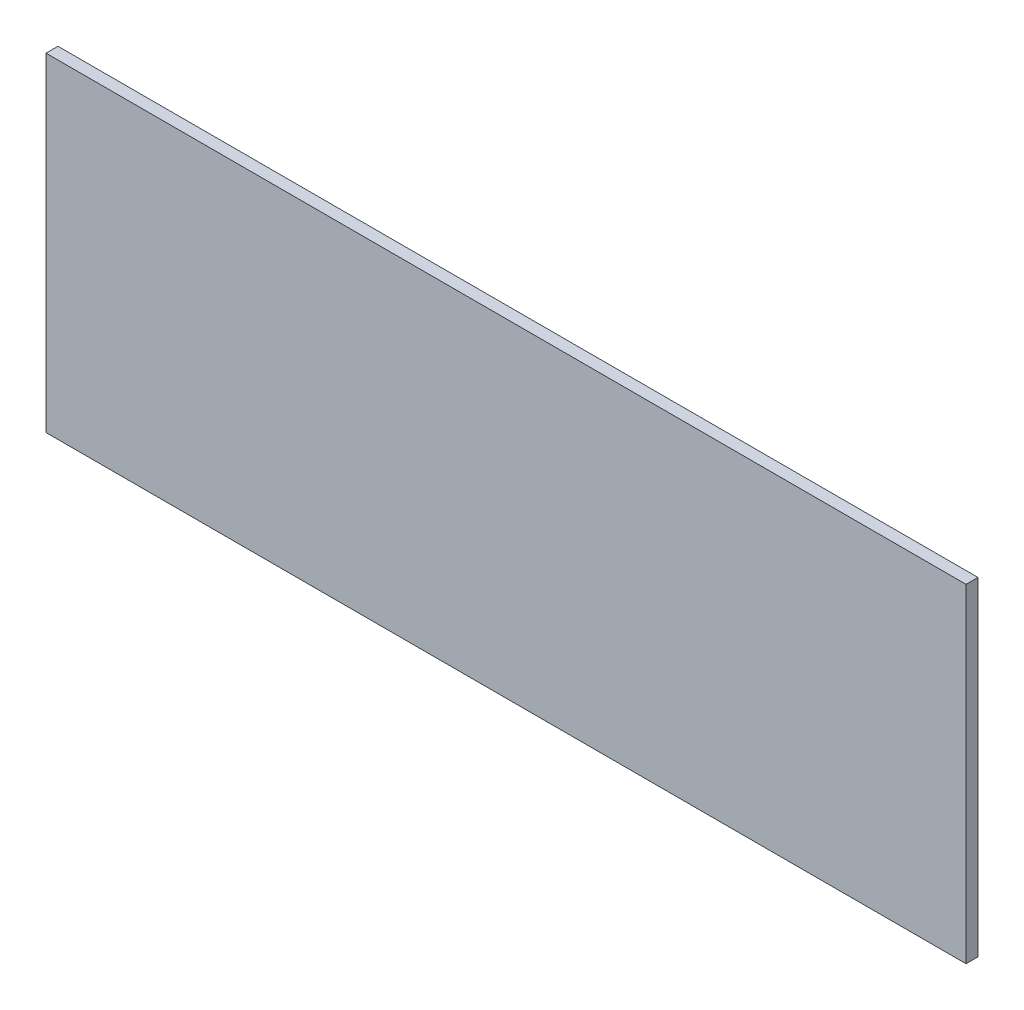
SolidWorks part; units mm, degrees
ref_plane "Front Plane" through (0, 0, 0) normal (0, 0, 1) x (1, 0, 0)
ref_plane "Top Plane" through (0, 0, 0) normal (0, 1, 0) x (1, 0, 0)
ref_plane "Right Plane" through (0, 0, 0) normal (1, 0, 0) x (0, 0, -1)
sketch "Sketch1" plane through (0, 0, 0) normal (0, 0, 1) x (1, 0, 0)
  line L1 (0, 0) -> (154, 0)
  line L2 (0, 0) -> (0, 55)
  line L3 (0, 55) -> (154, 55)
  line L4 (154, 0) -> (154, 55)
  dimension "D1" = 154
  dimension "D2" = 55
extrude "Profile" add sketch "Sketch1" along normal blind 2
equation "\"Profile_Depth\"= 2mm"
equation "\"D1@Profile\" = \"Profile_Depth\""
equation "\"Profile_Sketch_1\"= 154mm"
equation "\"D1@Sketch1\" = \"Profile_Sketch_1\""
equation "\"Profile_Sketch_2\"= 55mm"
equation "\"D2@Sketch1\" = \"Profile_Sketch_2\""
equation "\"EnvelopeWidth\"= 154mm"
equation "\"EnvelopeHeight\"= 55mm"
